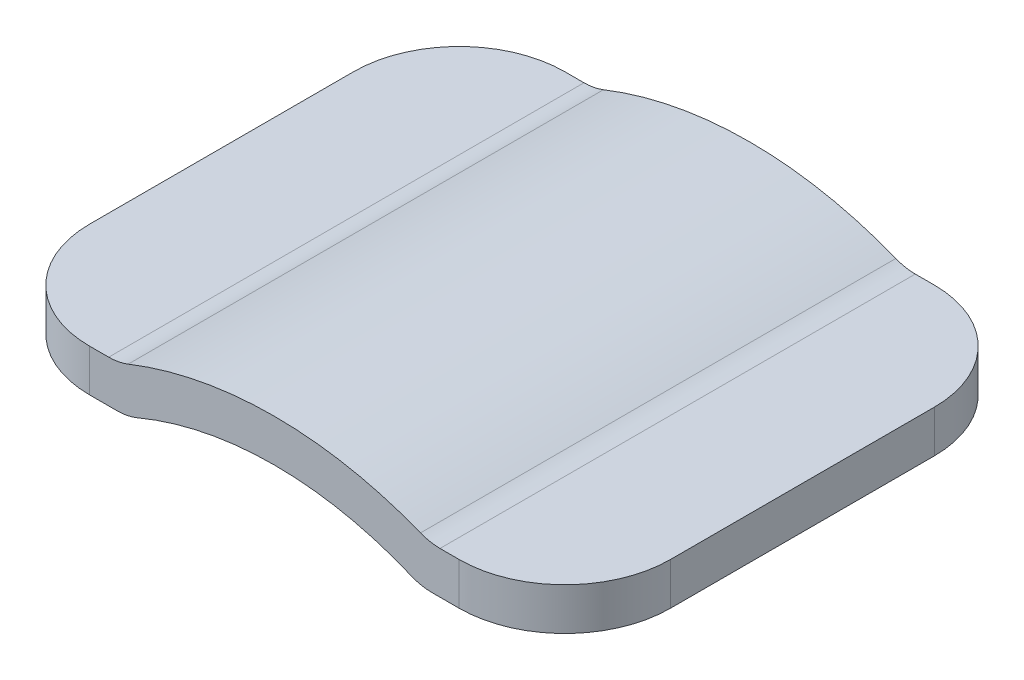
SolidWorks part; units mm, degrees
ref_plane "Спереди" through (0, 0, 0) normal (0, 0, 1) x (1, 0, 0)
ref_plane "Сверху" through (0, 0, 0) normal (0, 1, 0) x (1, 0, 0)
ref_plane "Справа" through (0, 0, 0) normal (1, 0, 0) x (0, 0, -1)
sketch "Эскиз1" plane through (0, 0, 0) normal (0, 0, 1) x (1, 0, 0)
  line L0 (0, 1851.0121) -> (0, -2923.7678) construction
  line L3 (-1100, -120) -> (-1100, 40)
  line L5 (1100, -120) -> (1100, 40)
  line L7 (-1100, 40) -> (-627.3755, 40)
  line L8 (-1100, -120) -> (-595.9866, -120)
  line L9 (1100, -120) -> (595.9866, -120)
  line L10 (1100, 40) -> (627.3755, 40)
  arc A0 (-518.5857, -104.4156) -> (518.5857, -104.4156) centre (0, -1340) cw
  arc A1 (-553.5666, 54.1176) -> (553.5666, 54.1176) centre (0, -1340) cw
  arc A2 (-627.3755, 40) -> (-553.5666, 54.1176) centre (-627.3755, 240) ccw
  arc A3 (-595.9866, -120) -> (-518.5857, -104.4156) centre (-595.9866, 80) ccw
  arc A4 (595.9866, -120) -> (518.5857, -104.4156) centre (595.9866, 80) cw
  arc A5 (627.3755, 40) -> (553.5666, 54.1176) centre (627.3755, 240) cw
  point P15 (0, 0)
  dimension "D1" = 1500
  dimension "D2" = 200
  dimension "D4" = 160
  dimension "D3" = 200
  dimension "D7" = 280
  dimension "D5" = 2200
  dimension "D6" = 160
extrude "Бобышка-Вытянуть1" add sketch "Эскиз1" along normal mid plane 1800
sketch "Эскиз3" plane through (0, 40, 0) normal (0, 1, 0) x (1, 0, 0)
  line L0 (0, 1405.5147) -> (0, -1507.1296) construction
  line L1 (700, 900) -> (-700, 900)
  line L3 (-1100, -900) -> (-1100, 900) construction
  line L4 (-1100, 500) -> (-1100, -500)
  line L5 (-627.3755, -900) -> (-1100, -900) construction
  line L6 (-700, -900) -> (700, -900)
  line L7 (-553.5666, -900) -> (553.5666, -900) construction
  line L9 (-627.3755, 900) -> (-1100, 900) construction
  line L10 (1100, 500) -> (1100, -500)
  arc A0 (-700, 900) -> (-1100, 500) centre (-700, 500) ccw
  arc A1 (-1100, -500) -> (-700, -900) centre (-700, -500) ccw
  arc A2 (1100, -500) -> (700, -900) centre (700, -500) cw
  arc A3 (700, 900) -> (1100, 500) centre (700, 500) cw
  point P5 (0, 0)
  point P6 (-1100, 500)
  point P20 (0, 0)
  point P23 (0, -900)
  point P28 (0, 900)
  dimension "D1" = 400
extrude "Вырез-Вытянуть3" cut sketch "Эскиз3" against normal through all flip side to cut
